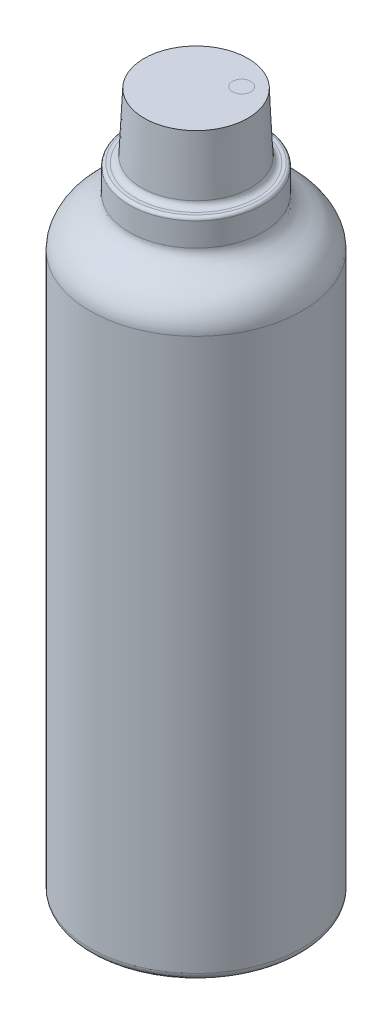
SolidWorks part; units mm, degrees
material "Water"
ref_plane "Front Plane" through (0, 0, 0) normal (0, 0, 1) x (1, 0, 0)
ref_plane "Top Plane" through (0, 0, 0) normal (0, 1, 0) x (1, 0, 0)
ref_plane "Right Plane" through (0, 0, 0) normal (1, 0, 0) x (0, 0, -1)
sketch "Sketch1" plane through (0, 0, 0) normal (0, 0, 1) x (1, 0, 0)
  line L0 (28.1765, 0) -> (32.4, 0)
  line L1 (0, 0) -> (0, 230) construction
  line L2 (34.9, 2.5) -> (34.9, 184)
  line L3 (0, 230) -> (17.06, 230)
  line L4 (17.06, 230) -> (17.9703, 210.656)
  line L5 (19.9681, 208.75) -> (21, 208.75)
  line L6 (22, 207.75) -> (22, 200)
  line L7 (25.3971, 0.8191) -> (27.1504, 0.1809)
  line L8 (0, 1) -> (24.371, 1)
  line L9 (0, 1) -> (0, 230)
  arc A0 (21, 208.75) -> (22, 207.75) centre (21, 207.75) cw
  arc A1 (17.9703, 210.656) -> (19.9681, 208.75) centre (19.9681, 210.75) ccw
  arc A2 (32.4, 0) -> (34.9, 2.5) centre (32.4, 2.5) ccw
  arc A3 (27.1504, 0.1809) -> (28.1765, 0) centre (28.1765, 3) ccw
  arc A4 (24.371, 1) -> (25.3971, 0.8191) centre (24.371, -2) cw
  spline S0 degree 3 poles (34.9, 184) (34.9, 186.9898) (31.9156, 192.2161) (25.8249, 195.0272) (22, 197.9122) (22, 200) knots 0 0 0 0 0.423783 0.726128 1 1 1 1
  point P13 (18.06, 208.75)
  point P16 (34.9, 0)
  point P26 (24.9, 1)
  dimension "D9" = 1
  dimension "D10" = 2
  dimension "D11" = 2.5
  dimension "D15" = 3
  dimension "D1" = 69.8
  dimension "D2" = 34.12
  dimension "D3" = 36.12
  dimension "D4" = 21.25
  dimension "D5" = 30
  dimension "D6" = 184
  dimension "D7" = 230
  dimension "D8" = 44
  dimension "D12" = 10
  dimension "D13" = 160
  dimension "D14" = 1
revolve "Revolve1" add sketch "Sketch1" angle 360 about L1
sketch "Sketch2" plane through (0, 230, 0) normal (0, 1, 0) x (1, 0, 0)
  circle A0 centre (7, 8) radius 3
  dimension "D1" = 6
  dimension "D2" = 8
  dimension "D3" = 7
split line "Split Line1"
